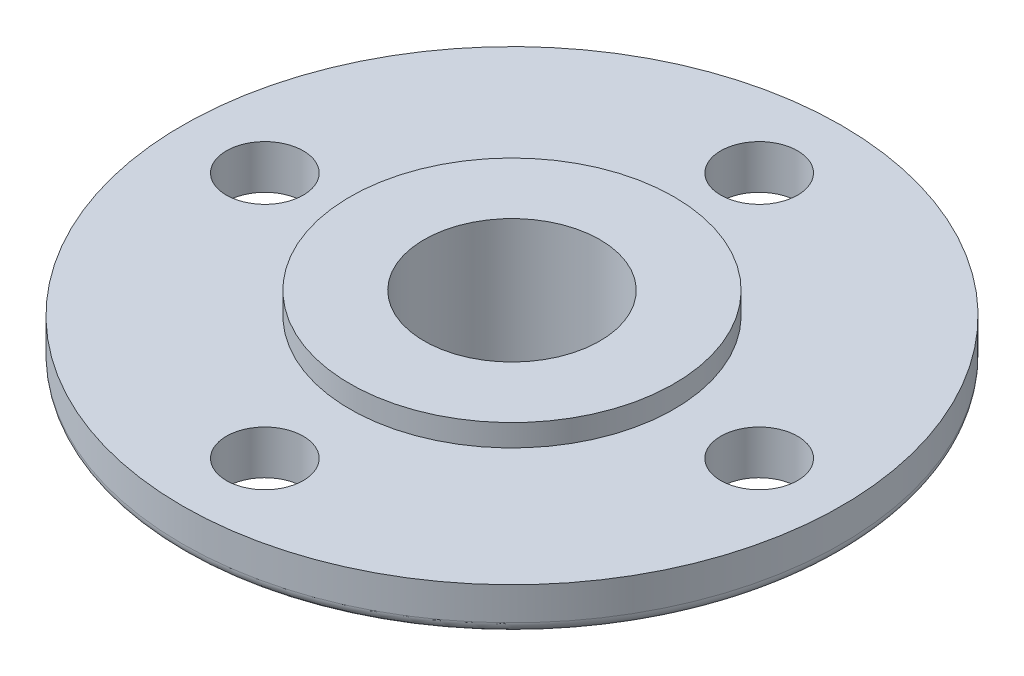
SolidWorks part; units mm, degrees
material " 12Х18Н10Т ГОСТ 4543-71"
ref_plane "Спереди" through (0, 0, 0) normal (0, 0, 1) x (1, 0, 0)
ref_plane "Сверху" through (0, 0, 0) normal (0, 1, 0) x (1, 0, 0)
ref_plane "Справа" through (0, 0, 0) normal (1, 0, 0) x (0, 0, -1)
sketch "Эскиз1" plane through (0, 0, 0) normal (0, 0, 1) x (1, 0, 0)
  line L0 (0, 0) -> (0, 60.5833) construction
  line L1 (-16, 0) -> (-16, 30)
  line L2 (-16, 30) -> (-29.5, 30)
  line L3 (-29.5, 30) -> (-29.5, 26)
  line L6 (-29.5, 26) -> (-60, 26)
  line L7 (-60, 26) -> (-60, 20)
  line L8 (-58, 18) -> (-26.4802, 18)
  line L9 (-24.5675, 16.5844) -> (-19.5, 0)
  line L10 (-19.5, 0) -> (-16, 0)
  arc A0 (-24.5675, 16.5844) -> (-26.4802, 18) centre (-26.4802, 16) ccw
  arc A1 (-60, 20) -> (-58, 18) centre (-58, 20) ccw
  point P15 (-25, 18)
  dimension "D12" = 2
  dimension "D13" = 2
  dimension "D1" = 120
  dimension "D2" = 32
  dimension "D3" = 39
  dimension "D4" = 50
  dimension "D5" = 30
  dimension "D6" = 59
  dimension "D7" = 4
  dimension "D8" = 8
revolve "Повернуть1" add sketch "Эскиз1" angle 360 about L0
sketch "Эскиз2" plane through (0, 26, 0) normal (0, 1, 0) x (1, 0, 0)
  circle A0 centre (0, 0) radius 45 construction
  circle A1 centre (-45, 0) radius 7
  circle A2 centre (0, 45) radius 7
  circle A3 centre (45, 0) radius 7
  circle A4 centre (0, -45) radius 7
  point P14 (0, 0)
  dimension "D1" = 90
  dimension "D2" = 14
  dimension "D3" = 4
extrude "Вырез-Вытянуть1" cut sketch "Эскиз2" against normal through all
